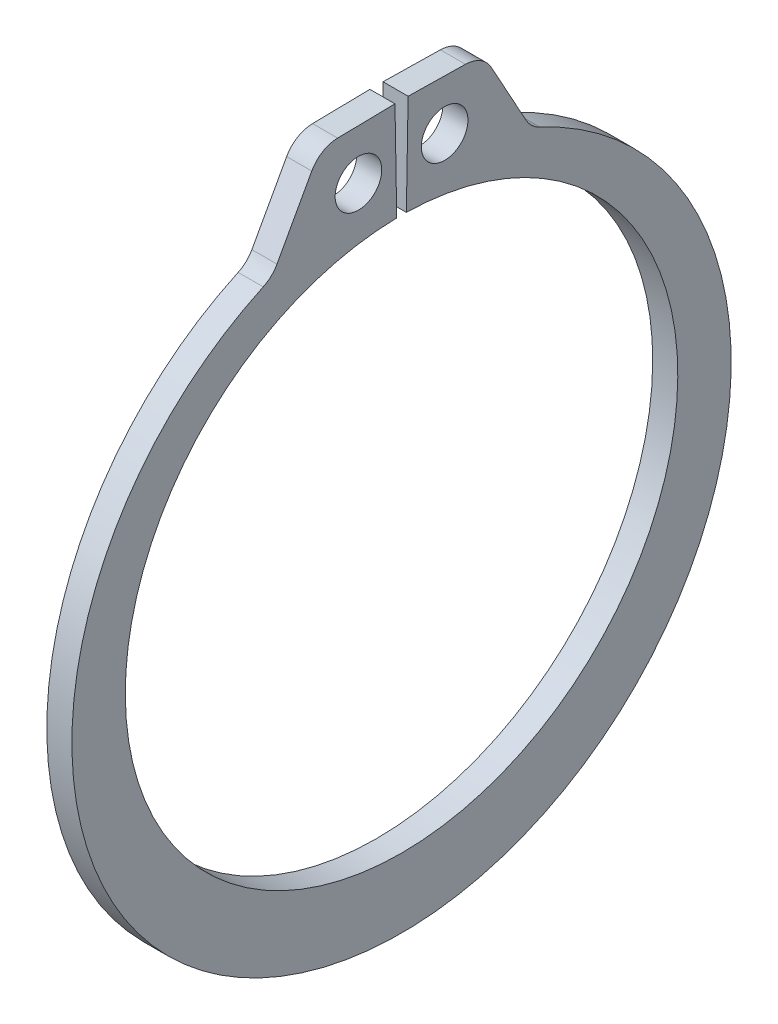
SolidWorks part; units mm, degrees
material "Plain Carbon Steel"
ref_plane "Front Plane" through (0, 0, 0) normal (0, 0, 1) x (1, 0, 0)
ref_plane "Top Plane" through (0, 0, 0) normal (0, 1, 0) x (1, 0, 0)
ref_plane "Right Plane" through (0, 0, 0) normal (1, 0, 0) x (0, 0, -1)
ref_plane "Plane1" through (-0.5334, 0, 0) normal (-1, 0, 0) x (0, -1, 0)
sketch "Sketch1" plane through (-0.5334, 0, 0) normal (-1, 0, 0) x (0, -1, 0)
  line L0 (-15.9443, 2.7169) -> (-15.9869, 0.2791)
  line L1 (-15.9869, 0.2791) -> (-11.7457, 0.205)
  line L2 (-11.7457, -0.205) -> (-15.9869, -0.2791)
  line L3 (-15.9869, -0.2791) -> (-15.9443, -2.7169)
  line L4 (-15.2803, -3.8182) -> (-12.5932, -5.2972)
  line L5 (-12.5932, 5.2972) -> (-15.2803, 3.8182)
  circle A0 centre (-13.8385, -1.8325) radius 0.9906
  arc A1 (-15.2803, 3.8182) -> (-15.9443, 2.7169) centre (-14.6618, 2.6945) ccw
  arc A2 (-11.7457, 0.205) -> (-11.7457, -0.205) centre (0, 0) cw
  arc A3 (-15.9443, -2.7169) -> (-15.2803, -3.8182) centre (-14.6618, -2.6945) ccw
  arc A4 (-12.5932, -5.2972) -> (-12.0475, -5.8826) centre (-13.2117, -6.4209) cw
  arc A5 (-12.0475, -5.8826) -> (-12.0475, 5.8826) centre (0.6762, 0) ccw
  arc A6 (-12.0475, 5.8826) -> (-12.5932, 5.2972) centre (-13.2117, 6.4209) cw
  circle A7 centre (-13.8385, 1.8325) radius 0.9906
extrude "Boss-Extrude1" add sketch "Sketch1" against normal blind 1.0668
